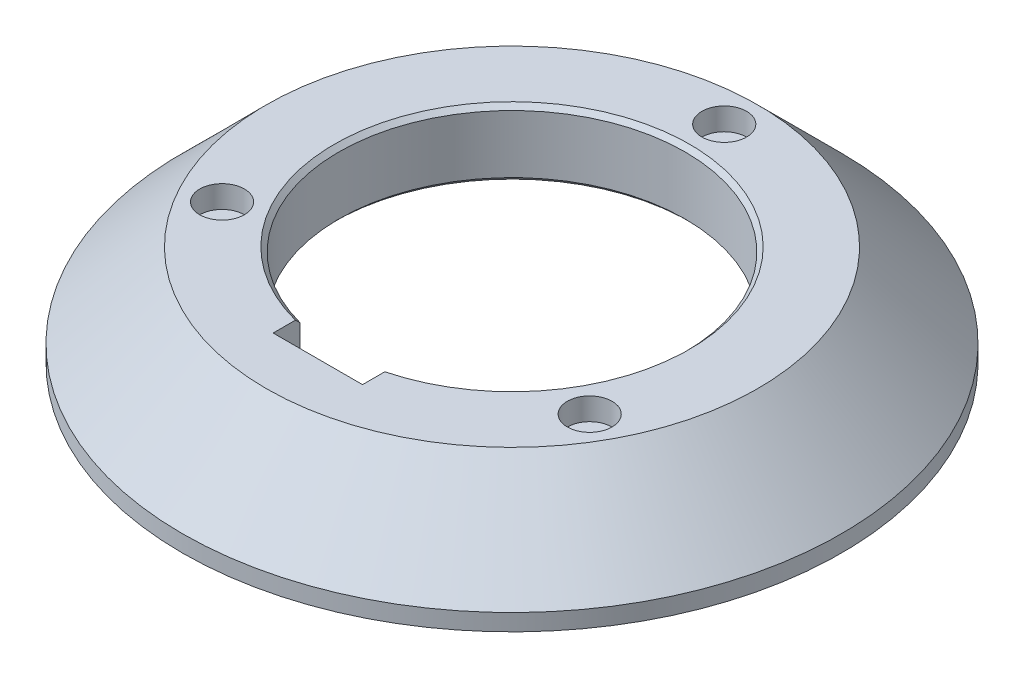
SolidWorks part; units mm, degrees
ref_plane "Спереди" through (0, 0, 0) normal (0, 0, 1) x (1, 0, 0)
ref_plane "Сверху" through (0, 0, 0) normal (0, 1, 0) x (1, 0, 0)
ref_plane "Справа" through (0, 0, 0) normal (1, 0, 0) x (0, 0, -1)
sketch "Эскиз1" plane through (0, 0, 0) normal (0, 0, 1) x (1, 0, 0)
  line L0 (0, 107.7506) -> (0, -115.6347) construction
  line L1 (77.5, 30) -> (77.5, 0)
  line L2 (77.5, 0) -> (117.5, 0)
  line L3 (117.5, 0) -> (132.5, -15)
  line L4 (132.5, -15) -> (147.5, -15)
  line L5 (147.5, -15) -> (147.5, -7.5)
  line L6 (147.5, -7.5) -> (110, 30)
  line L7 (110, 30) -> (77.5, 30)
  dimension "D1" = 295
  dimension "D2" = 220
  dimension "D3" = 45
  dimension "D4" = 235
  dimension "D5" = 155
  dimension "D6" = 45
  dimension "D7" = 15
revolve "Повернуть1" add sketch "Эскиз1" angle 360 about L0
chamfer "Фаска1" distance 2 angle 45 2 edges at (0, 0, 77.5) (0, 30, 77.5)
sketch "Эскиз2" plane through (0, 30, 0) normal (0, 1, 0) x (1, 0, 0)
  line L0 (0, 183.2159) -> (0, -176.2625) construction
  circle A0 centre (0, 0) radius 95 construction
  circle A1 centre (0, 95) radius 10
  dimension "D1" = 190
  dimension "D2" = 20
extrude "Вырез-Вытянуть1" cut sketch "Эскиз2" against normal blind 10
pattern_circular "Круговой массив1" count 3 over 360 about axis through (0, 0, 0) along (0, 1, 0) of "Вырез-Вытянуть1"
sketch "Эскиз3" plane through (0, 30, 0) normal (0, 1, 0) x (1, 0, 0)
  line L0 (0, 55.0843) -> (0, -155.657) construction
  line L1 (-209.5472, 0) -> (211.9356, 0) construction
  line L2 (0, 77.5) -> (-170.7128, 77.5) construction
  line L3 (-20, -86.9) -> (20, -86.9)
  line L4 (20, -86.9) -> (20, -62.046)
  line L5 (20, -62.046) -> (-20, -62.046)
  line L6 (-20, -62.046) -> (-20, -86.9)
  circle A0 centre (0, 0) radius 77.5 construction
  dimension "D1" = 164.4
  dimension "D2" = 40
extrude "Вырез-Вытянуть2" cut sketch "Эскиз3" against normal through all both and the other way through all
sketch "Эскиз4" plane through (0, 0, 0) normal (0, -1, 0) x (1, 0, 0)
  line L0 (0, 168.4384) -> (0, -196.8857) construction
  circle A0 centre (0, 0) radius 100 construction
  circle A1 centre (0, 100) radius 4
  dimension "D1" = 200
  dimension "D2" = 8
extrude "Вырез-Вытянуть3" cut sketch "Эскиз4" against normal blind 8
pattern_circular "Круговой массив2" count 8 over 360 about axis through (0, 0, 0) along (0, 1, 0) of "Вырез-Вытянуть3"
